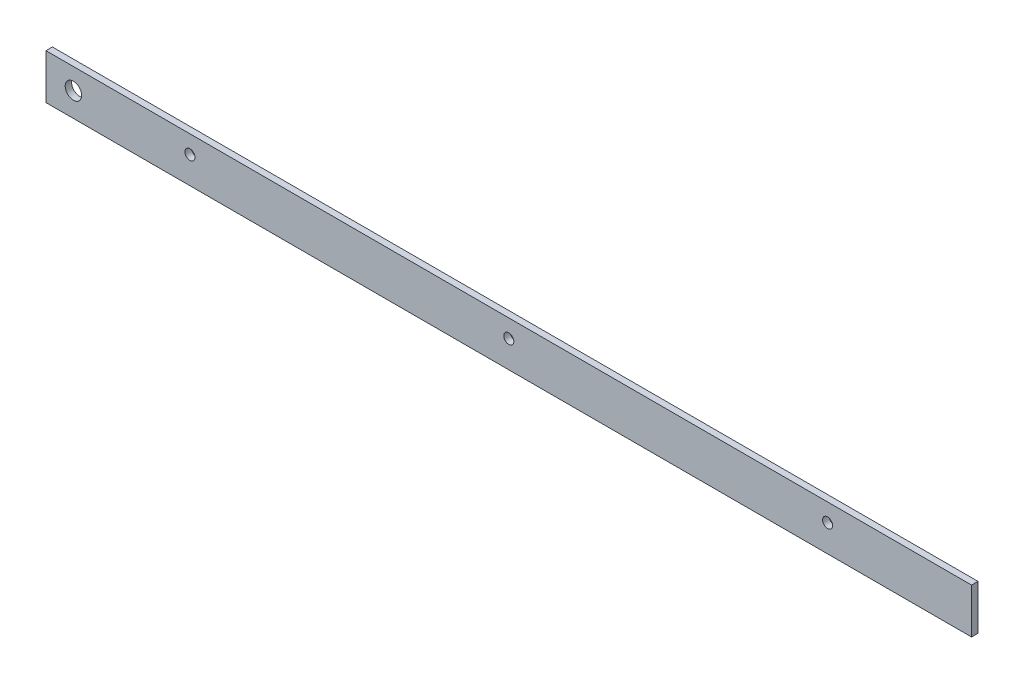
SolidWorks part; units mm, degrees
ref_plane "Front Plane" through (0, 0, 0) normal (0, 0, 1) x (1, 0, 0)
ref_plane "Top Plane" through (0, 0, 0) normal (0, 1, 0) x (1, 0, 0)
ref_plane "Right Plane" through (0, 0, 0) normal (1, 0, 0) x (0, 0, -1)
sketch "Sketch1" plane through (0, 0, 0) normal (0, 0, 1) x (1, 0, 0)
  line L6 (419.96, 17.392) -> (0, 17.392) construction
  line L9 (0, -4.833) -> (457.2, -4.833)
  line L10 (457.2, 9.447) -> (457.2, -4.833)
  line L12 (419.96, 17.392) -> (0, 17.392)
  line L13 (0, -4.833) -> (0, 17.392)
  line L14 (419.96, 17.392) -> (432.66, 17.392)
  line L15 (432.66, 9.447) -> (432.66, 17.392)
  line L16 (432.66, 24.067) -> (432.66, 17.067) construction
  line L17 (432.66, 9.447) -> (457.2, 9.447)
  line L18 (0, 20.567) -> (457.2, 20.567) construction
  line L19 (0, 20.567) -> (457.2, 20.567) construction
  circle A0 centre (13.54, 34.107) radius 13.54 construction
  circle A1 centre (13.54, 34.107) radius 13.54 construction
  circle A2 centre (13.54, 34.107) radius 4.0635 construction
  circle A3 centre (71.12, 8.5095) radius 2.4892 construction
  circle A4 centre (228.6, 8.5095) radius 2.4892 construction
  circle A5 centre (386.08, 8.5095) radius 2.4892 construction
  circle A6 centre (71.12, 8.5095) radius 2.4892
  circle A7 centre (228.6, 8.5095) radius 2.4892
  circle A8 centre (386.08, 8.5095) radius 2.4892
  circle A9 centre (13.54, 7.027) radius 4.0635
  dimension "D1" = 8.127
extrude "Boss-Extrude1" add sketch "Sketch1" along normal blind 3.175 contours L17 L15 L14 L12 L13 L9 L10 A8 A7 A6
sketch "Sketch4" plane through (432.66, 0, 0) normal (1, 0, 0) x (0, 0, -1)
  line L4 (0, 9.447) -> (0, 17.392)
  line L5 (0, 17.392) -> (-3.175, 17.392)
  line L6 (-3.175, 17.392) -> (-3.175, 9.447)
  line L7 (-3.175, 9.447) -> (0, 9.447)
  line L8 (0, 9.447) -> (0, 17.392)
  line L9 (0, 17.392) -> (-3.175, 17.392)
  line L10 (-3.175, 17.392) -> (-3.175, 9.447)
  line L11 (-3.175, 9.447) -> (0, 9.447)
  dimension "D1" = 0
extrude "Boss-Extrude3" add sketch "Sketch4" along normal up to surface (24.54 mm away) up to face at (457.2, 2.307, 1.5875)
